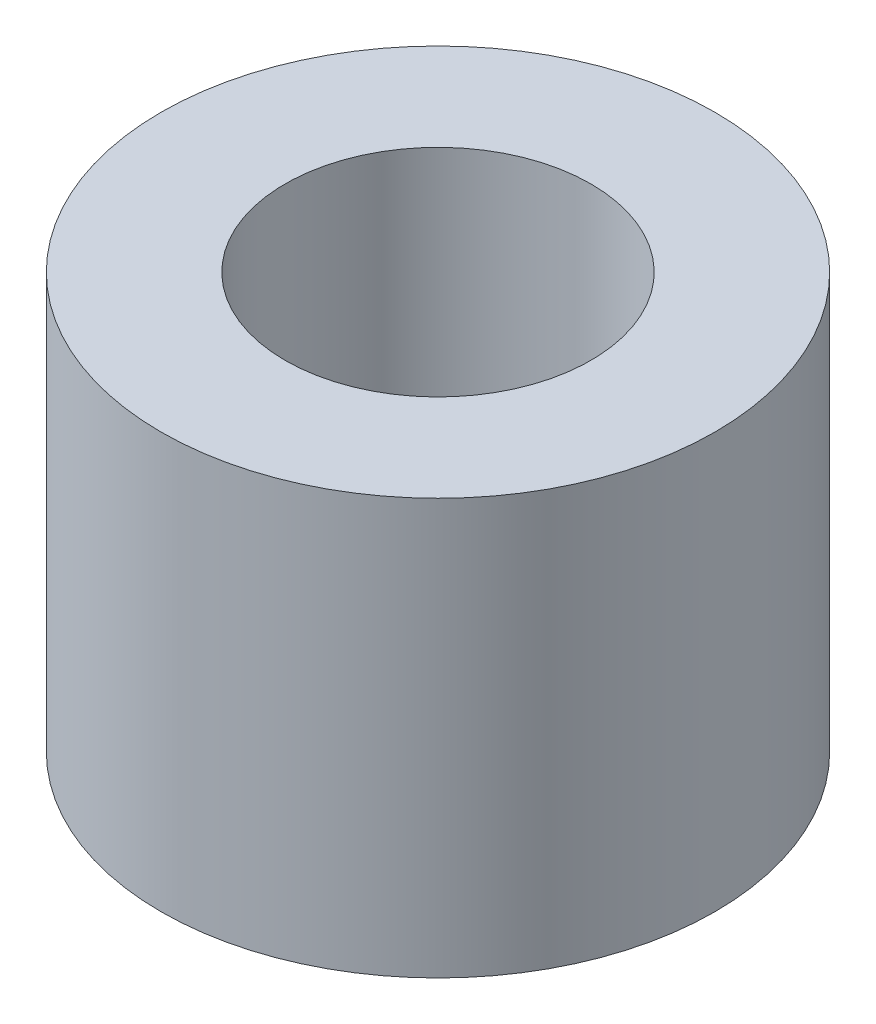
SolidWorks part; units mm, degrees
ref_plane "Front" through (0, 0, 0) normal (0, 0, 1) x (1, 0, 0)
ref_plane "Top" through (0, 0, 0) normal (0, 1, 0) x (1, 0, 0)
ref_plane "Right" through (0, 0, 0) normal (1, 0, 0) x (0, 0, -1)
sketch "Sketch1" plane through (0, 0, 0) normal (0, 1, 0) x (1, 0, 0)
  circle A0 centre (0, 0) radius 3.175
  circle A1 centre (0, 0) radius 1.7526
  dimension "OD" = 6.35
  dimension "ID" = 3.5052
extrude "Thickness" add sketch "Sketch1" along normal blind 4.7625
